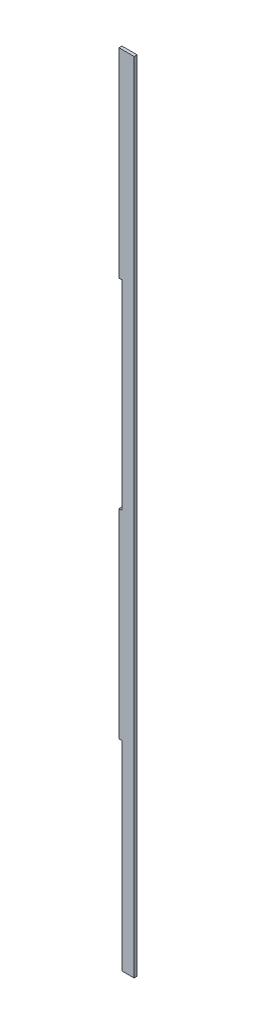
SolidWorks part; units mm, degrees
ref_plane "Front Plane" through (0, 0, 0) normal (0, 0, 1) x (1, 0, 0)
ref_plane "Top Plane" through (0, 0, 0) normal (0, 1, 0) x (1, 0, 0)
ref_plane "Right Plane" through (0, 0, 0) normal (1, 0, 0) x (0, 0, -1)
sketch "Sketch1" plane through (0, 0, 0) normal (0, 1, 0) x (1, 0, 0)
  line L1 (-4.0438, -0.7937) -> (4.0438, -0.7937)
  line L2 (-4.0438, -0.7937) -> (-4.0438, 0.7937)
  line L3 (-4.0438, 0.7937) -> (4.0438, 0.7937)
  line L4 (4.0438, -0.7937) -> (4.0438, 0.7937)
  line L5 (-4.0438, -0.7937) -> (4.0438, 0.7937) construction
  line L6 (-4.0438, 0.7937) -> (4.0438, -0.7937) construction
  point P0 (0, 0)
  dimension "D1" = 1.5875
  dimension "D2" = 8.0875
extrude "Boss-Extrude1" add sketch "Sketch1" along normal blind 427.1518
sketch "Sketch2" plane through (0, 0, 0.7937) normal (0, 0, 1) x (1, 0, 0)
  line L0 (-4.0438, 0) -> (4.0438, 0) construction
  line L1 (-4.0438, 427.1518) -> (-2.4563, 427.1518) construction
  line L2 (-4.0438, 427.1518) -> (-4.0438, 0) construction
  line L3 (-4.0438, 0) -> (-2.4562, 0) construction
  line L4 (-2.4563, 427.1518) -> (-2.4562, 0) construction
  line L5 (-2.4562, 213.5759) -> (-2.4563, 427.1518) construction
  line L6 (-2.4562, 0) -> (-2.4562, 213.5759) construction
  line L7 (-4.0438, 213.5759) -> (-2.4562, 213.5759) construction
  line L8 (-4.0438, 0) -> (-2.4562, 0)
  line L9 (-4.0438, 0) -> (-4.0437, 106.7879)
  line L10 (-4.0437, 106.7879) -> (-2.4562, 106.7879)
  line L11 (-2.4562, 0) -> (-2.4562, 106.7879)
  line L12 (-4.0437, 320.3639) -> (-2.4562, 320.3639)
  line L13 (-4.0438, 213.5759) -> (-4.0437, 320.3639)
  line L14 (-4.0438, 213.5759) -> (-2.4562, 213.5759)
  line L15 (-2.4562, 213.5759) -> (-2.4562, 320.3639)
  line L16 (-4.0438, 427.1518) -> (4.0438, 427.1518) construction
  dimension "D1" = 1.5875
  dimension "D2" = 213.5759
  dimension "D3" = 106.7879
  dimension "D4" = 106.7879
extrude "Cut-Extrude1" cut sketch "Sketch2" against normal blind 427.1518
